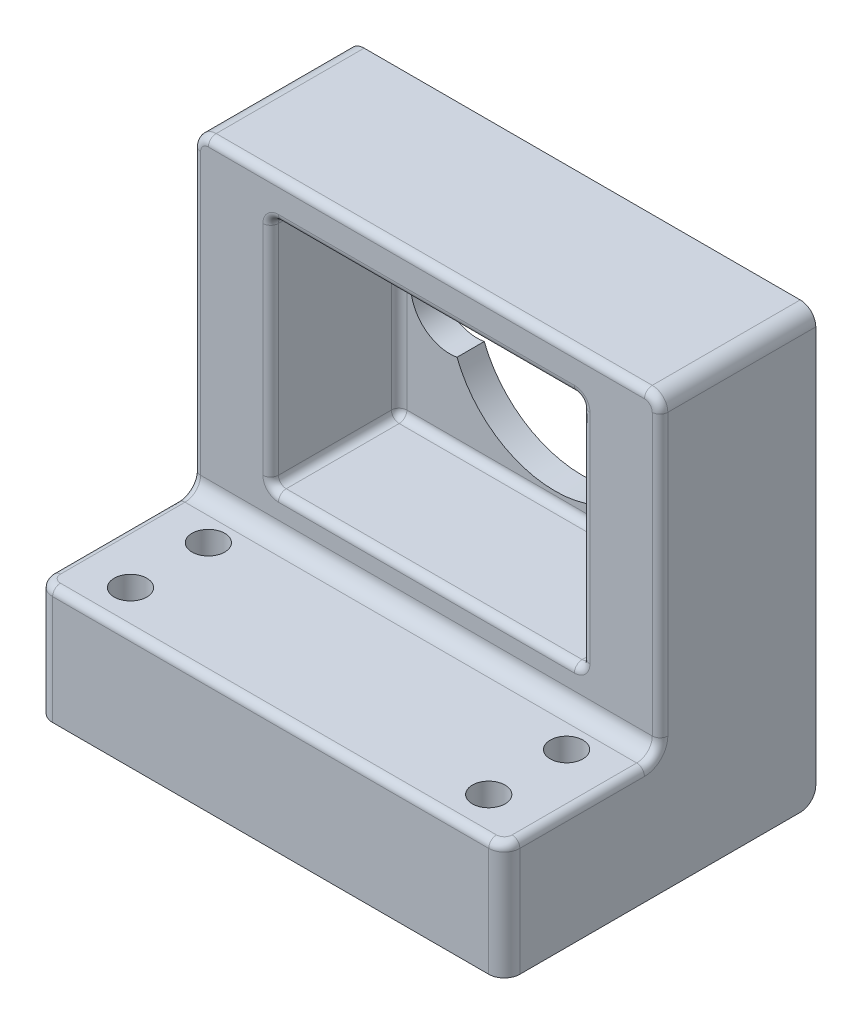
SolidWorks part; units mm, degrees
ref_plane "Front Plane" through (0, 0, 0) normal (0, 0, 1) x (1, 0, 0)
ref_plane "Top Plane" through (0, 0, 0) normal (0, 1, 0) x (1, 0, 0)
ref_plane "Right Plane" through (0, 0, 0) normal (1, 0, 0) x (0, 0, -1)
sketch "Sketch1" plane through (0, 0, 0) normal (0, 0, 1) x (1, 0, 0)
  line L1 (-25, 17.5) -> (35, 17.5)
  line L2 (-25, 17.5) -> (-25, -22.5)
  line L3 (-25, -22.5) -> (35, -22.5)
  line L4 (35, 17.5) -> (35, -22.5)
  dimension "D1" = 60
  dimension "D2" = 40
  dimension "D3" = 17.5
  dimension "D4" = 25
extrude "Boss-Extrude1" add sketch "Sketch1" along normal blind 20
sketch "Sketch2" plane through (0, 0, 20) normal (0, 0, 1) x (1, 0, 0)
  line L2 (35, -22.5) -> (35, 17.5) construction
  line L3 (35, 17.5) -> (-25, 17.5) construction
  arc A0 (-7.5741, -7.4135) -> (17.5741, -7.4135) centre (5, -2.5) ccw
  arc A1 (-7.5741, 2.4135) -> (-7.5741, -7.4135) centre (-8.5, -2.5) ccw
  arc A2 (17.5741, -7.4135) -> (17.5741, 2.4135) centre (18.5, -2.5) ccw
  arc A3 (17.5741, 2.4135) -> (-7.5741, 2.4135) centre (5, -2.5) ccw
  dimension "D1" = 30
  dimension "D2" = 27
  dimension "D4" = 10
  dimension "D5" = 10
  dimension "D3" = 20
extrude "Cut-Extrude1" cut sketch "Sketch2" against normal blind 30
sketch "Sketch3" plane through (0, 0, 0) normal (0, 0, -1) x (-1, 0, 0)
  line L0 (25, 17.5) -> (25, -22.5) construction
  line L1 (-35, -22.5) -> (25, -22.5)
  line L2 (-35, -22.5) -> (-35, -37.5)
  line L3 (-35, -37.5) -> (25, -37.5)
  line L4 (25, -22.5) -> (25, -37.5)
  dimension "D1" = 15
extrude "Boss-Extrude2" add sketch "Sketch3" against normal blind 40
sketch "Sketch4" plane through (0, -22.5, 0) normal (0, 1, 0) x (1, 0, 0)
  line L0 (35, -40) -> (35, -20) construction
  line L1 (-25, -40) -> (-25, -20) construction
  line L2 (-25, -40) -> (35, -40) construction
  line L3 (-25, -20) -> (35, -20) construction
  circle A0 centre (-18, -35) radius 2.1
  circle A1 centre (-18, -25) radius 2.1
  circle A2 centre (28, -35) radius 2.1
  circle A3 centre (28, -25) radius 2.1
  dimension "D1" = 4.2
  dimension "D2" = 4.2
  dimension "D3" = 4.2
  dimension "D4" = 4.2
  dimension "D5" = 7
  dimension "D6" = 7
  dimension "D7" = 7
  dimension "D8" = 7
  dimension "D9" = 5
  dimension "D10" = 5
  dimension "D11" = 5
extrude "Cut-Extrude2" cut sketch "Sketch4" against normal blind 20
fillet "Fillet1" radius 2 1 edges at (5, -22.5, 20)
fillet "Fillet2" radius 2 5 edges at (-25, 17.5, 10) (35, 17.5, 10) (35, -30, 40) (-25, -30, 40) (5, -37.5, 0)
sketch "Esquisse1" plane through (0, 0, 20) normal (0, 0, 1) x (1, 0, 0)
  line L1 (25, 12.5) -> (-15, 12.5)
  line L2 (25, 12.5) -> (25, -17.5)
  line L3 (25, -17.5) -> (-15, -17.5)
  line L4 (-15, 12.5) -> (-15, -17.5)
  line L5 (25, 12.5) -> (-15, -17.5) construction
  line L6 (25, -17.5) -> (-15, 12.5) construction
  point P0 (5, -2.5)
  dimension "D1" = 40
  dimension "D2" = 30
extrude "Enlèv. mat.-Extru.1" cut sketch "Esquisse1" against normal blind 16.5
fillet "Congé1" radius 1 24 edges at (5, -17.5, 20) (5, 12.5, 20) (-24.4142, 16.9142, 20) (5, 17.5, 20) (34.4142, 16.9142, 20) (35, -2.5, 20) (35, -21.9142, 20.5858) (35, -22.5, 30) (34.4142, -22.5, 39.4142) (5, -22.5, 40) (-24.4142, -22.5, 39.4142) (-25, -22.5, 30) (-25, -21.9142, 20.5858) (-25, -2.5, 20) (-15, -17.5, 11.75) (25, 12.5, 11.75) (25, -2.5, 20) (25, -17.5, 11.75) (5, -17.5, 3.5) (25, -2.5, 3.5) (-15, -2.5, 20) (-15, 12.5, 11.75) (5, 12.5, 3.5) (-15, -2.5, 3.5)
